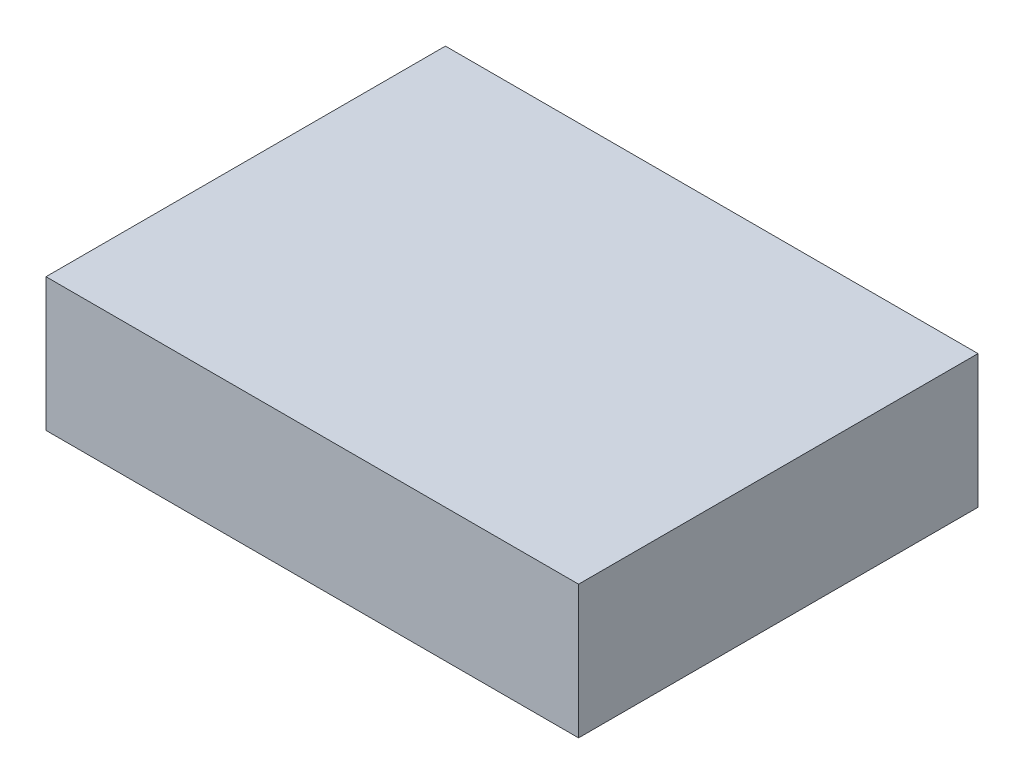
SolidWorks part; units mm, degrees
ref_plane "Front Plane" through (0, 0, 0) normal (0, 0, 1) x (1, 0, 0)
ref_plane "Top Plane" through (0, 0, 0) normal (0, 1, 0) x (1, 0, 0)
ref_plane "Right Plane" through (0, 0, 0) normal (1, 0, 0) x (0, 0, -1)
other "Configuration Table"
sketch "Sketch1" plane through (0, 0, 0) normal (0, 0, 1) x (1, 0, 0)
  line L1 (-25.4, 0) -> (177.8, 0)
  line L2 (-25.4, 0) -> (-25.4, -50.8)
  line L3 (-25.4, -50.8) -> (177.8, -50.8)
  line L4 (177.8, 0) -> (177.8, -50.8)
  dimension "D1" = 50.8
  dimension "D2" = 203.2
extrude "Extrude1" add sketch "Sketch1" along normal blind 152.4
